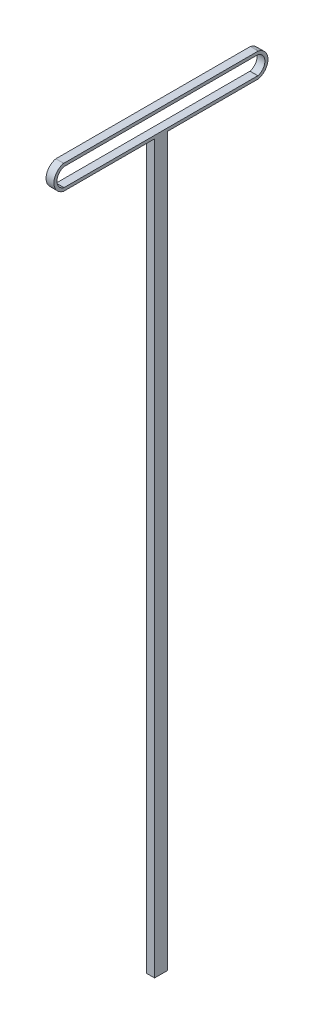
SolidWorks part; units mm, degrees
ref_plane "Front Plane" through (0, 0, 0) normal (0, 0, 1) x (1, 0, 0)
ref_plane "Top Plane" through (0, 0, 0) normal (0, 1, 0) x (1, 0, 0)
ref_plane "Right Plane" through (0, 0, 0) normal (1, 0, 0) x (0, 0, -1)
sketch "Sketch1" plane through (0, 0, 0) normal (1, 0, 0) x (0, 0, -1)
  line L0 (0, 0) -> (142.6334, 0) construction
  line L1 (-160, 15) -> (160, 15)
  line L2 (-160, -15) -> (160, -15)
  line L3 (0, -15) -> (0, 56.0524) construction
  line L4 (-160.5799, -20) -> (160.5799, -20)
  line L5 (-160.5799, 20) -> (160.5799, 20)
  arc A0 (160, 15) -> (160, -15) centre (156.1959, 0) cw
  arc A1 (-160, 15) -> (-160, -15) centre (-156.1959, 0) ccw
  arc A2 (-160.5799, 20) -> (-160.5799, -20) centre (-156.1959, 0) ccw
  arc A3 (160.5799, 20) -> (160.5799, -20) centre (156.1959, 0) cw
  point P12 (0, 15)
  dimension "D1" = 30
  dimension "D2" = 160
  dimension "D3" = 5
extrude "Boss-Extrude1" add sketch "Sketch1" along normal mid plane 13
sketch "Sketch3" plane through (0, -20, 0) normal (0, -1, 0) x (1, 0, 0)
  line L0 (6.5, 160.5799) -> (6.5, -160.5799) construction
  line L1 (-6.5, 10.4939) -> (6.5, 10.4939)
  line L2 (-6.5, 10.4939) -> (-6.5, -10.4939)
  line L3 (-6.5, -10.4939) -> (6.5, -10.4939)
  line L4 (6.5, 10.4939) -> (6.5, -10.4939)
  line L5 (-6.5, 10.4939) -> (6.5, -10.4939) construction
  line L6 (-6.5, -10.4939) -> (6.5, 10.4939) construction
  point P0 (0, 0)
  dimension "D1" = 13
  dimension "D2" = 20.9877
extrude "Boss-Extrude2" add sketch "Sketch3" along normal blind 1200
